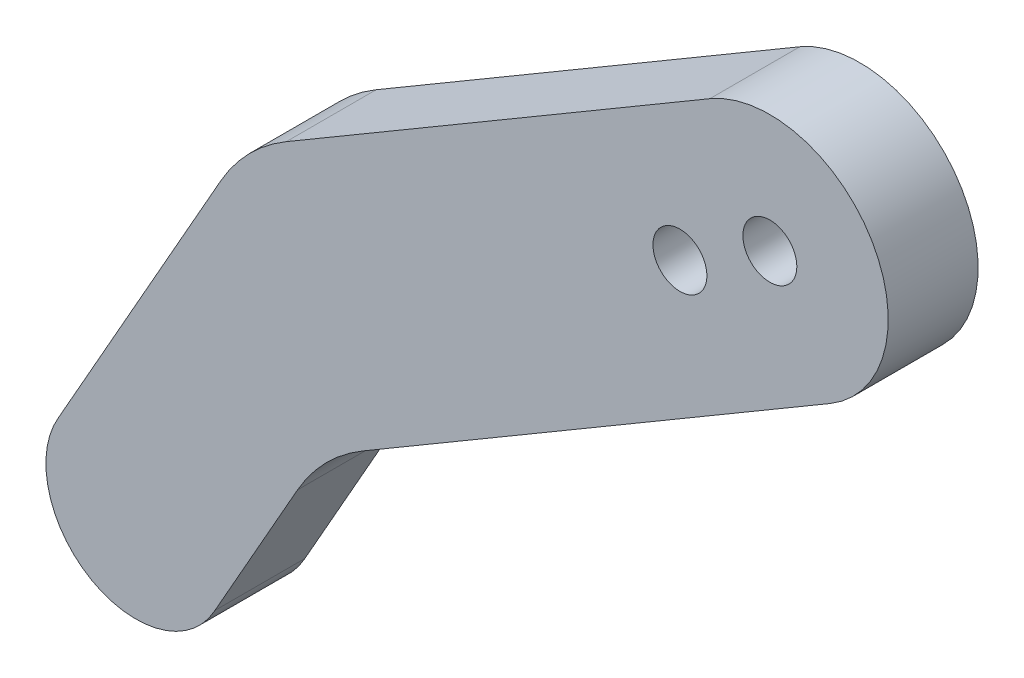
SolidWorks part; units mm, degrees
ref_plane "Front Plane" through (0, 0, 0) normal (0, 0, 1) x (1, 0, 0)
ref_plane "Top Plane" through (0, 0, 0) normal (0, 1, 0) x (1, 0, 0)
ref_plane "Right Plane" through (0, 0, 0) normal (1, 0, 0) x (0, 0, -1)
sketch "Sketch3" plane through (0, 0, 0) normal (0, 0, 1) x (1, 0, 0)
  line L0 (0, 0) -> (9.0356, 15.9373)
  line L1 (0, 0) -> (8.6992, -4.932) construction
  line L2 (8.6992, -4.932) -> (13.296, 3.1761)
  line L3 (12.6671, 19.6262) -> (36.2195, 33.4715)
  line L4 (36.2195, 33.4715) -> (42.8888, 22.1263) construction
  line L5 (16.9275, 6.8649) -> (42.8888, 22.1263)
  arc A0 (36.2195, 33.4715) -> (42.8888, 22.1263) centre (39.5541, 27.7989) cw
  arc A1 (0, 0) -> (8.6992, -4.932) centre (4.3053, -2.5441) ccw
  arc A2 (9.0356, 15.9373) -> (12.6671, 19.6262) centre (17.7348, 11.0054) cw
  arc A3 (13.296, 3.1761) -> (16.9275, 6.8649) centre (21.9952, -1.7558) cw
  point P10 (10.3571, 18.2683)
  point P13 (19.9017, -5.697)
  point P15 (14.6175, 5.5071)
  dimension "D7" = 5.0008
  dimension "D8" = 10
  dimension "D9" = 10
  dimension "D1" = 21
  dimension "D2" = 30
  dimension "D3" = 150
  dimension "D5" = 12
  dimension "D6" = 10
extrude "Boss-Extrude1" add sketch "Sketch3" along normal blind 5 contours L0 A1 L2 L5 A0 L3
sketch "Sketch4" plane through (0, 0, 5) normal (0, 0, 1) x (1, 0, 0)
  line L0 (36.2195, 33.4715) -> (42.8888, 22.1263) construction
  line L1 (39.5541, 27.7989) -> (24.4816, 18.9385) construction
  line L2 (36.2195, 33.4715) -> (42.8888, 22.1263) construction
  circle A0 centre (39.5541, 27.7989) radius 1.5
  arc A1 (42.8888, 22.1263) -> (36.2195, 33.4715) centre (39.5541, 27.7989) ccw construction
  circle A2 centre (34.5541, 24.8596) radius 1.5
  point P9 (39.5541, 27.7989)
  dimension "D1" = 3
  dimension "D2" = 5
  dimension "D3" = 3
extrude "Cut-Extrude1" cut sketch "Sketch4" against normal blind 7
